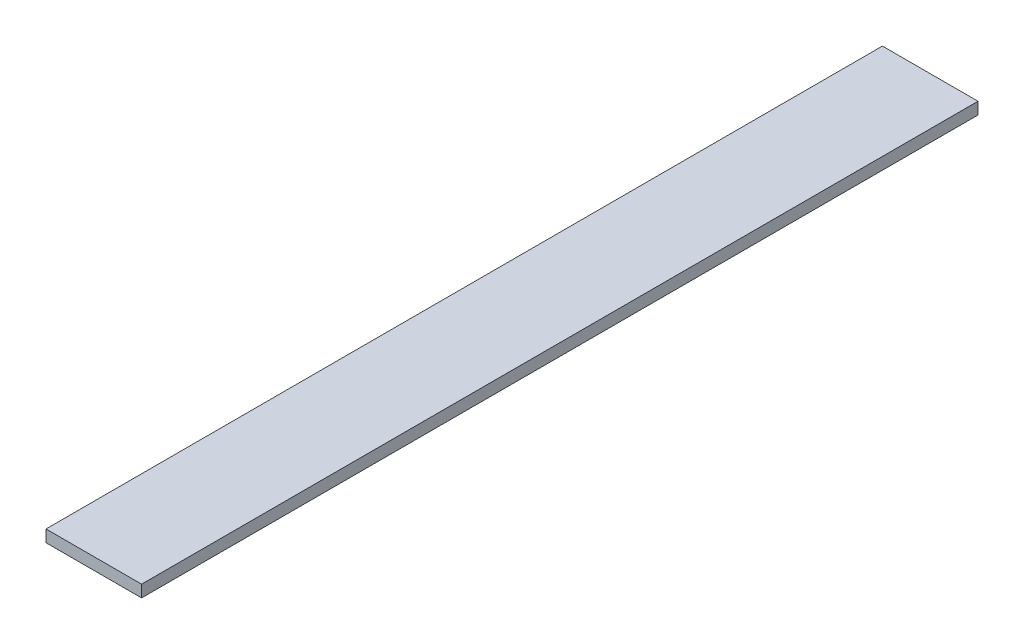
SolidWorks part; units mm, degrees
ref_plane "Front Plane" through (0, 0, 0) normal (0, 0, 1) x (1, 0, 0)
ref_plane "Top Plane" through (0, 0, 0) normal (0, 1, 0) x (1, 0, 0)
ref_plane "Right Plane" through (0, 0, 0) normal (1, 0, 0) x (0, 0, -1)
sketch "Sketch1" plane through (0, 0, 0) normal (0, 0, 1) x (1, 0, 0)
  line L0 (-2.5, 5) -> (2.5, 5) construction
  line L1 (-2, 5) -> (2, 5)
  line L2 (-2, 5) -> (-2, 5.5)
  line L3 (-2, 5.5) -> (2, 5.5)
  line L4 (2, 5) -> (2, 5.5)
  line L5 (1.7657, 5.7343) -> (2.5, 5) construction
  line L7 (0, -30.25) -> (0, 30.25) construction
  point P8 (0, 5)
  dimension "D1" = 0.5
  dimension "D2" = 4
extrude "Boss-Extrude1" add sketch "Sketch1" against normal up to surface (35 mm away) contours L2 L3 L4 L1
